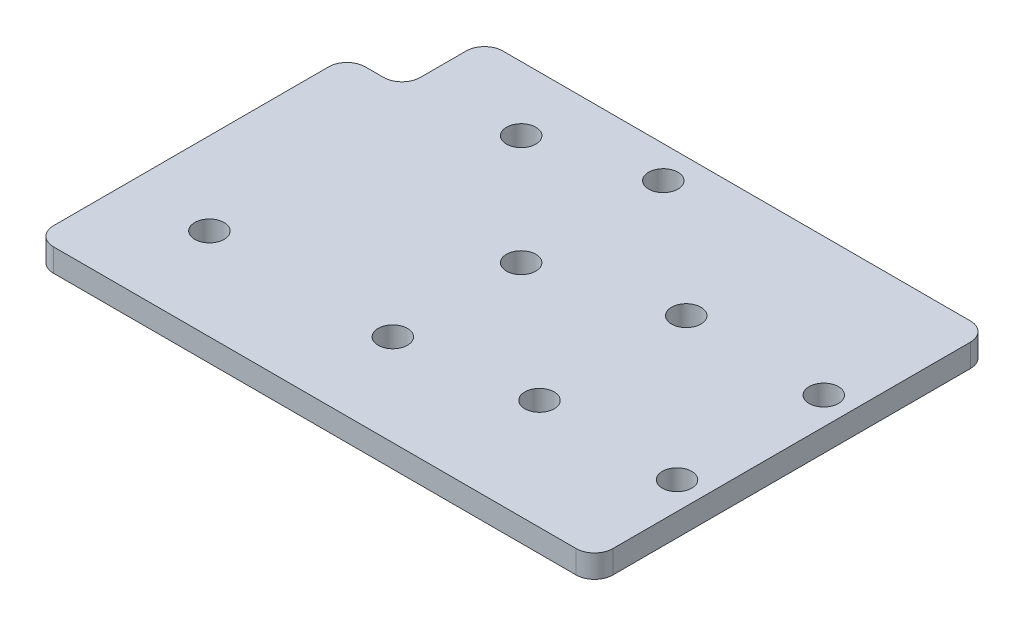
SolidWorks part; units mm, degrees
ref_plane "前视基准面" through (0, 0, 0) normal (0, 0, 1) x (1, 0, 0)
ref_plane "上视基准面" through (0, 0, 0) normal (0, 1, 0) x (1, 0, 0)
ref_plane "右视基准面" through (0, 0, 0) normal (1, 0, 0) x (0, 0, -1)
sketch "草图1" plane through (0, 0, 0) normal (0, 1, 0) x (-1, 0, 0)
  line L0 (27.5, 21.5) -> (27.5, -12.5) construction
  line L1 (-27.5, 21.5) -> (27.5, 21.5)
  line L2 (-27.5, 21.5) -> (-27.5, -21.5)
  line L3 (-27.5, -21.5) -> (27.5, -21.5)
  line L4 (27.5, -12.5) -> (27.5, -21.5)
  line L5 (27.5, 21.5) -> (33.5, 21.5)
  line L6 (27.5, 21.5) -> (27.5, -12.5) construction
  line L7 (27.5, -12.5) -> (33.5, -12.5)
  line L8 (33.5, 21.5) -> (33.5, -12.5)
  line L9 (27.5, 21.5) -> (33.5, -12.5) construction
  line L10 (27.5, -12.5) -> (33.5, 21.5) construction
  circle A0 centre (-24.5, 9.5) radius 1.6
  circle A1 centre (-9.5, 9.5) radius 1.6
  circle A2 centre (-24.5, -6.5) radius 1.6
  circle A3 centre (-9.5, -6.5) radius 1.6
  circle A4 centre (4.5, -2.5) radius 1.6
  circle A5 centre (4.5, 11.5) radius 1.6
  circle A6 centre (24.5, 11.5) radius 1.6
  circle A7 centre (16.5, -14.5) radius 1.6
  circle A8 centre (4.5, -18) radius 1.6
  point P13 (0, 0)
  point P33 (-27.5, 0)
  point P35 (0, 21.5)
  point P43 (30.5, 4.5)
  dimension "D5" = 3.2
  dimension "D17" = 3.2
  dimension "D1" = 43
  dimension "D2" = 55
  dimension "D3" = 15
  dimension "D4" = 16
  dimension "D6" = 3
  dimension "D7" = 12
  dimension "D8" = 10
  dimension "D9" = 20
  dimension "D10" = 32
  dimension "D11" = 14
  dimension "D12" = 12
  dimension "D13" = 12
  dimension "D14" = 12.5
  dimension "D16" = 6
  dimension "D18" = 34
extrude "凸台-拉伸1" add sketch "草图1" along normal blind 2.5
fillet "圆角1" radius 2 6 edges at (27.5, 1.25, -21.5) (27.5, 1.25, 21.5) (-27.5, 1.25, -21.5) (-33.5, 1.25, 21.5) (-33.5, 1.25, -12.5) (-27.5, 1.25, -12.5)
